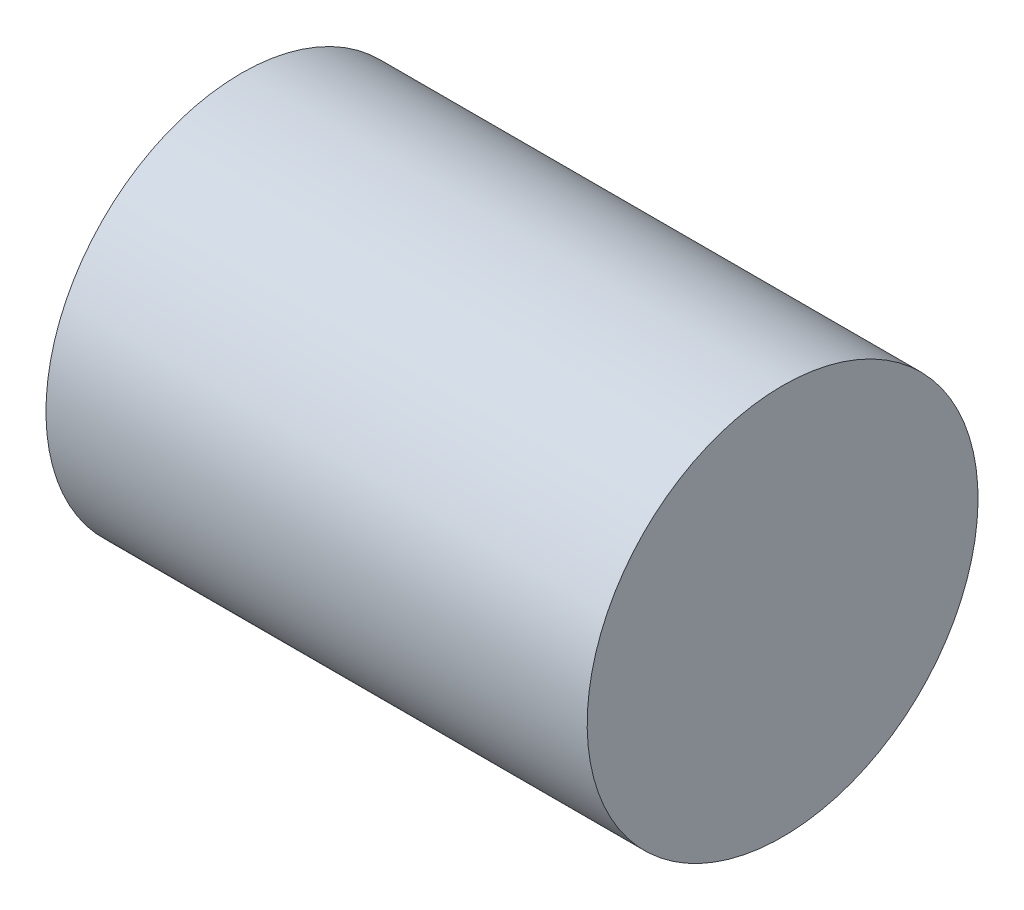
SolidWorks part; units mm, degrees
material "Alloy Steel"
ref_plane "Front Plane" through (0, 0, 0) normal (0, 0, 1) x (1, 0, 0)
ref_plane "Top Plane" through (0, 0, 0) normal (0, 1, 0) x (1, 0, 0)
ref_plane "Right Plane" through (0, 0, 0) normal (1, 0, 0) x (0, 0, -1)
sketch "Sketch1" plane through (0, 0, 0) normal (0, 0, 1) x (1, 0, 0)
  line L0 (0, 0) -> (0, 65)
  line L1 (0, 65) -> (180, 65)
  line L2 (180, 65) -> (180, 0)
  line L3 (180, 0) -> (0, 0) construction
  line L4 (0, 0) -> (180, 0)
  dimension "D1" = 180
  dimension "D2" = 130
revolve "Revolve1" add sketch "Sketch1" angle 360 about L3
